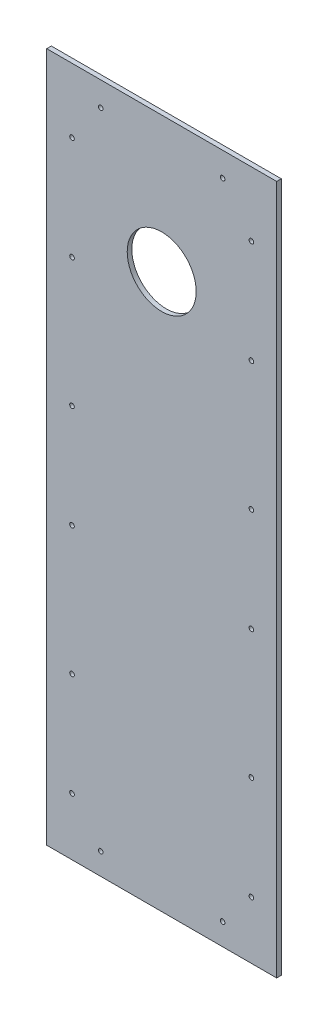
SolidWorks part; units mm, degrees
material "Alumina"
ref_plane "Front Plane" through (0, 0, 0) normal (0, 0, 1) x (1, 0, 0)
ref_plane "Top Plane" through (0, 0, 0) normal (0, 1, 0) x (1, 0, 0)
ref_plane "Right Plane" through (0, 0, 0) normal (1, 0, 0) x (0, 0, -1)
sketch "Sketch1" plane through (0, 0, 0) normal (0, 0, 1) x (1, 0, 0)
  line L1 (50, -150) -> (-50, -150)
  line L2 (50, -150) -> (50, 150)
  line L3 (50, 150) -> (-50, 150)
  line L4 (-50, -150) -> (-50, 150)
  line L5 (50, -150) -> (-50, 150) construction
  line L6 (50, 150) -> (-50, -150) construction
  point P0 (0, 0)
  dimension "D1" = 100
  dimension "D2" = 300
extrude "Boss-Extrude1" add sketch "Sketch1" along normal blind 2
sketch "Sketch2" plane through (0, 0, 2) normal (0, 0, 1) x (1, 0, 0)
  line L0 (-50, 150) -> (-50, -150) construction
  line L1 (50, 150) -> (-50, 150) construction
  line L2 (-50, -150) -> (50, -150) construction
  line L5 (-39, 122) -> (-39, 21) construction
  circle A0 centre (-39, 122) radius 1
  circle A1 centre (-39, 77) radius 1
  circle A2 centre (39, 122) radius 1
  circle A3 centre (39, 77) radius 1
  circle A4 centre (-39, 21) radius 1
  circle A5 centre (-39, -24) radius 1
  circle A6 centre (39, 21) radius 1
  circle A7 centre (39, -24) radius 1
  circle A8 centre (-39, -80) radius 1
  circle A9 centre (-39, -125) radius 1
  circle A10 centre (39, -80) radius 1
  circle A11 centre (39, -125) radius 1
  dimension "D1" = 2
  dimension "D3" = 28
  dimension "D4" = 2
  dimension "D6" = 11
  dimension "D14" = 78
  dimension "D15" = 11
  dimension "D2" = 11
  dimension "D9" = 25
  dimension "D17" = 101
  dimension "D7" = 2
  dimension "D8" = 3
extrude "Cut-Extrude1" cut sketch "Sketch2" against normal blind 10
sketch "Sketch3" plane through (0, 0, 0) normal (0, 0, -1) x (-1, 0, 0)
  line L0 (-50, 150) -> (50, 150) construction
  line L1 (-50, -150) -> (-50, 150) construction
  circle A0 centre (0, 91) radius 15
  dimension "D2" = 30
  dimension "D3" = 50
  dimension "D1" = 59
extrude "Cut-Extrude2" cut sketch "Sketch3" against normal blind 10
sketch "Sketch4" plane through (0, 0, 0) normal (0, 0, -1) x (-1, 0, 0)
  line L0 (-26.5, -140.5) -> (26.5, -140.5) construction
  line L1 (26.5, -140.5) -> (26.5, 139.5) construction
  line L2 (26.5, 139.5) -> (-26.5, 139.5) construction
  line L3 (-26.5, 139.5) -> (-26.5, -140.5) construction
  line L4 (50, -150) -> (-50, -150) construction
  line L5 (-50, 150) -> (50, 150) construction
  line L6 (-50, -150) -> (-50, 150) construction
  line L7 (50, 150) -> (50, -150) construction
  circle A0 centre (-26.5, 139.5) radius 1
  circle A1 centre (26.5, 139.5) radius 1
  circle A2 centre (-26.5, -140.5) radius 1
  circle A3 centre (26.5, -140.5) radius 1
  dimension "D5" = 2
  dimension "D6" = 2
  dimension "D7" = 2
  dimension "D8" = 2
  dimension "D1" = 9.5
  dimension "D2" = 10.5
  dimension "D3" = 23.5
  dimension "D4" = 23.5
extrude "Cut-Extrude3" cut sketch "Sketch4" against normal blind 10
